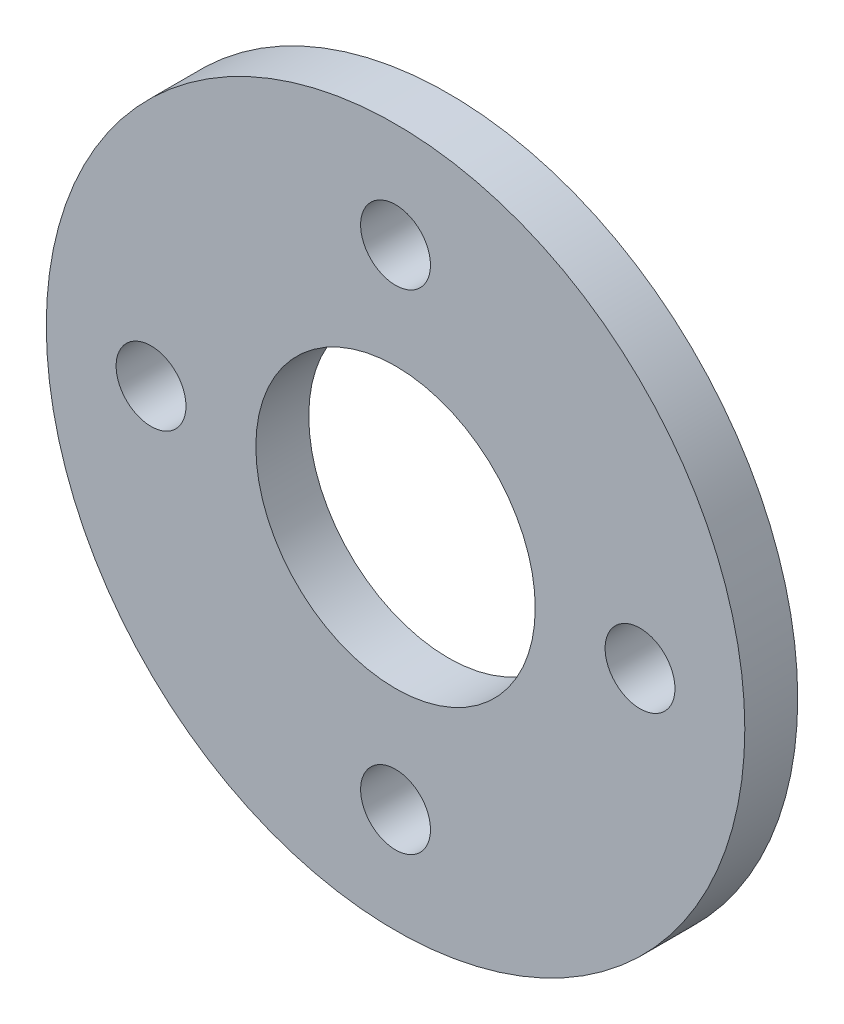
SolidWorks part; units mm, degrees
ref_plane "Ön Düzlem" through (0, 0, 0) normal (0, 0, 1) x (1, 0, 0)
ref_plane "Üst Düzlem" through (0, 0, 0) normal (0, 1, 0) x (1, 0, 0)
ref_plane "Sağ Düzlem" through (0, 0, 0) normal (1, 0, 0) x (0, 0, -1)
sketch "Çizim1" plane through (0, 0, 0) normal (0, 0, 1) x (1, 0, 0)
  circle A0 centre (0, 0) radius 10
  circle A1 centre (0, 0) radius 4
  circle A2 centre (-7, 0) radius 1
  circle A3 centre (0, 7) radius 1
  circle A4 centre (7, 0) radius 1
  circle A5 centre (0, -7) radius 1
  point P15 (0, 0)
  dimension "D1" = 20
  dimension "D2" = 8
  dimension "D4" = 2
  dimension "D3" = 7
  dimension "D5" = 4
extrude "Yükseklik-Ekstrüzyon1" add sketch "Çizim1" along normal blind 1.515
